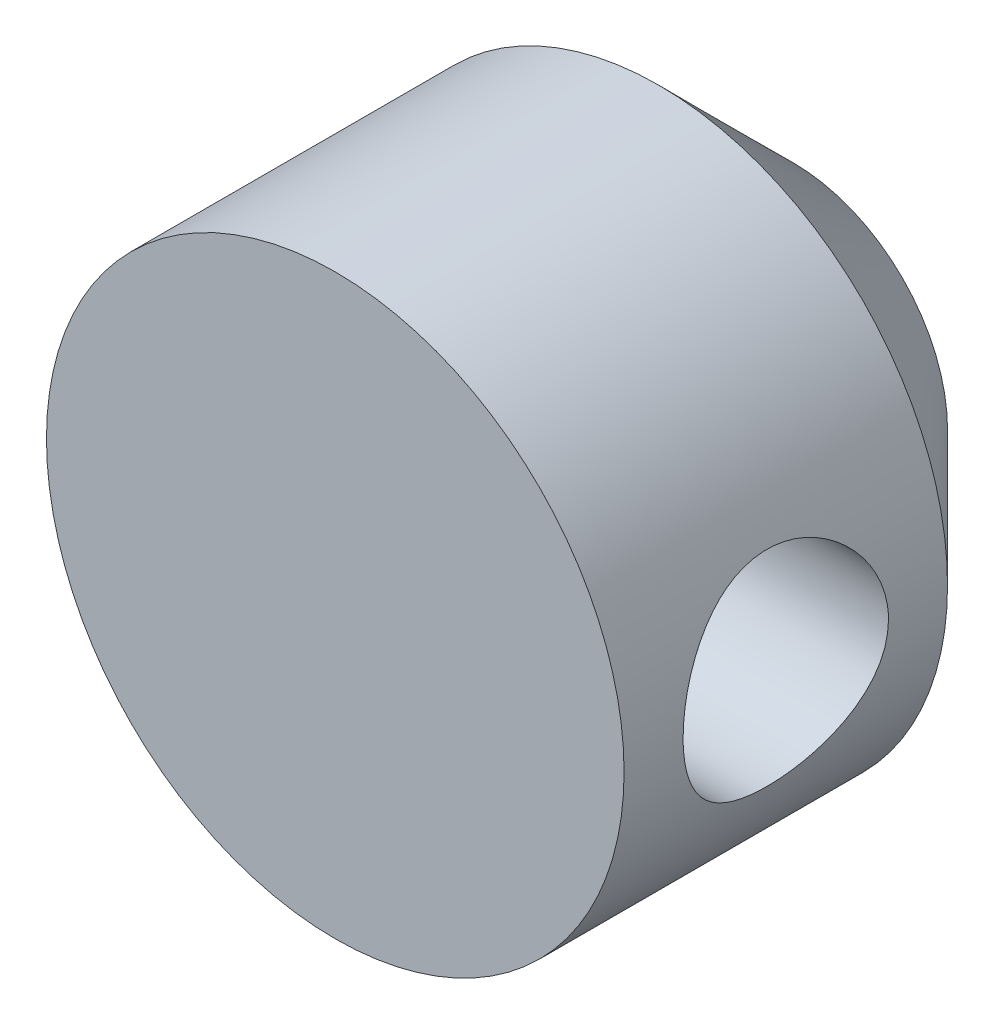
SolidWorks part; units mm, degrees
material "AISI 4340 Steel, normalized"
ref_plane "Front Plane" through (0, 0, 0) normal (0, 0, 1) x (1, 0, 0)
ref_plane "Top Plane" through (0, 0, 0) normal (0, 1, 0) x (1, 0, 0)
ref_plane "Right Plane" through (0, 0, 0) normal (1, 0, 0) x (0, 0, -1)
sketch "Sketch1" plane through (0, 0, 0) normal (0, 0, 1) x (1, 0, 0)
  circle A2 centre (0, 0) radius 28.575
extrude "Boss-Extrude1" add sketch "Sketch1" along normal blind 25 draft 45 draft outward yes
sketch "Sketch3" plane through (0, 0, 25) normal (0, 0, 1) x (1, 0, 0)
  circle A1 centre (0, 0) radius 53.575
  circle A2 centre (0, 0) radius 53.575
  dimension "D1" = 0
extrude "Boss-Extrude2" add sketch "Sketch3" along normal blind 60
sketch "Sketch4" plane through (0, 0, 0) normal (1, 0, 0) x (0, 0, -1)
  line L0 (-25, 53.575) -> (-25, -53.575) construction
  circle A0 centre (-55, 0) radius 19.05
  dimension "D1" = 38.1
  dimension "D2" = 30
extrude "Cut-Extrude1" cut sketch "Sketch4" against normal through all both and the other way through all
